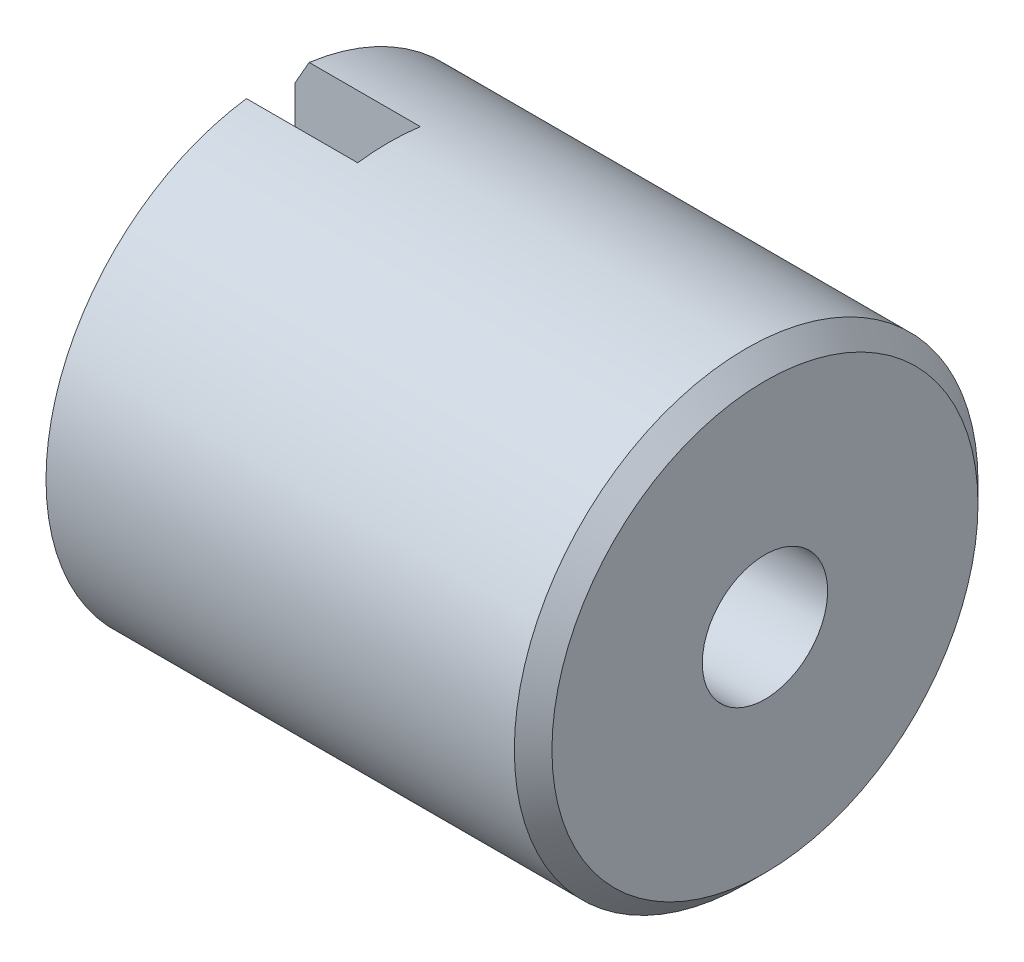
SolidWorks part; units mm, degrees
ref_plane "Plan de face" through (0, 0, 0) normal (0, 0, 1) x (1, 0, 0)
ref_plane "Plan de dessus" through (0, 0, 0) normal (0, 1, 0) x (1, 0, 0)
ref_plane "Plan de droite" through (0, 0, 0) normal (1, 0, 0) x (0, 0, -1)
sketch "Esquisse1" plane through (0, 0, 0) normal (0, 0, 1) x (1, 0, 0)
  line L0 (0, 4) -> (0, 0)
  line L1 (0, 0) -> (12, 0)
  line L2 (12, 0) -> (8, 4)
  line L3 (8, 4) -> (0, 4)
  line L4 (0, 0) -> (12, 0) construction
revolve "Révolution1" add sketch "Esquisse1" angle 360 about L4
chamfer "Chanfrein1" distance 0.6905 angle 30 1 edges at (0, 0, -4)
sketch "Esquisse3" plane through (0, 0, 0) normal (-1, 0, 0) x (0, 0, 1)
  circle A0 centre (0, 0) radius 2.55
  dimension "D1" = 5.1
extrude "Enlèv. mat.-Extru.2" cut sketch "Esquisse3" against normal blind 2.2
ref_plane "Plan1" through (8, 0, 0) normal (-1, 0, 0) x (0, 0, 1)
sketch "Esquisse4" plane through (8, 0, 0) normal (-1, 0, 0) x (0, 0, 1)
  circle A0 centre (0, 0) radius 4 construction
  circle A1 centre (0, 0) radius 4
extrude "Enlèv. mat.-Extru.3" cut sketch "Esquisse4" against normal blind 12.2
chamfer "Chanfrein2" distance 0.6 angle 45 1 edges at (8, 0, 4)
sketch "Esquisse5" plane through (0, 0, 0) normal (-1, 0, 0) x (0, 0, 1)
  circle A0 centre (0, 0) radius 3.7
  dimension "D1" = 7.4
extrude "Enlèv. mat.-Extru.4" cut sketch "Esquisse5" against normal through all flip side to cut
sketch "Esquisse6" plane through (0, 0, 0) normal (-1, 0, 0) x (0, 0, 1)
  line L1 (-0.5, 4.411) -> (0.5, 4.411)
  line L2 (-0.5, 4.411) -> (-0.5, 2.208)
  line L3 (-0.5, 2.208) -> (0.5, 2.208)
  line L4 (0.5, 4.411) -> (0.5, 2.208)
  line L5 (-0.5, 4.411) -> (0.5, 2.208) construction
  line L6 (-0.5, 2.208) -> (0.5, 4.411) construction
  circle A0 centre (0, 0) radius 3.3095 construction
  point P4 (0, 3.3095)
  point P5 (0, 3.3095)
  dimension "D1" = 1
extrude "Enlèv. mat.-Extru.5" cut sketch "Esquisse6" against normal blind 2
sketch "Esquisse7" plane through (2.2, 0, 0) normal (-1, 0, 0) x (0, 0, 1)
  circle A0 centre (0, 0) radius 1
  dimension "D1" = 2
extrude "Enlèv. mat.-Extru.6" cut sketch "Esquisse7" against normal through all
